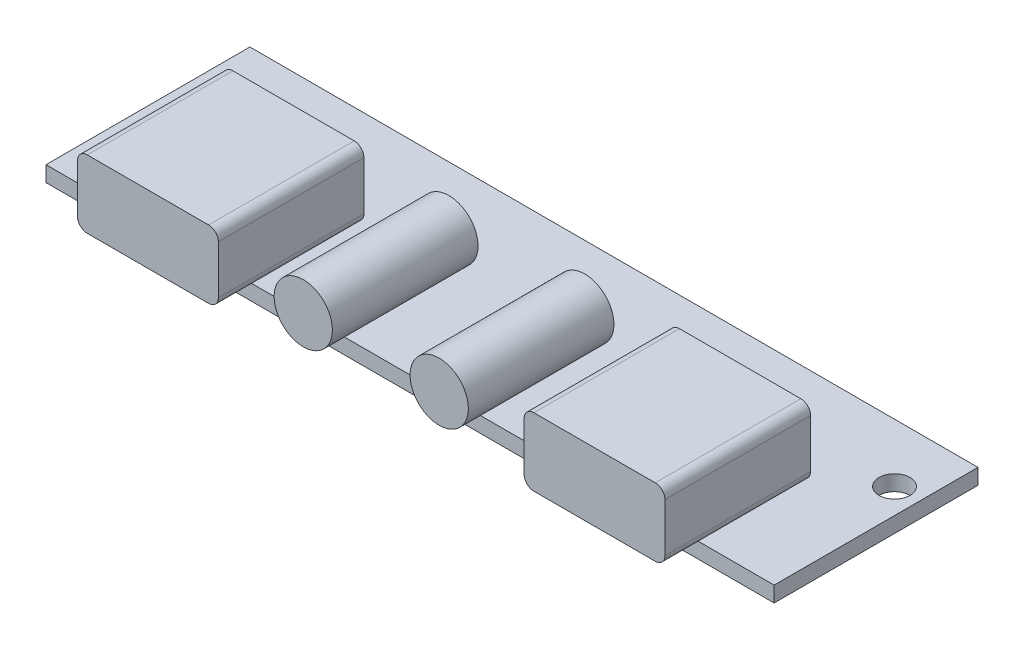
SolidWorks part; units mm, degrees
ref_plane "Front Plane" through (0, 0, 0) normal (0, 0, 1) x (1, 0, 0)
ref_plane "Top Plane" through (0, 0, 0) normal (0, 1, 0) x (1, 0, 0)
ref_plane "Right Plane" through (0, 0, 0) normal (1, 0, 0) x (0, 0, -1)
sketch "Sketch1" plane through (0, 0, 0) normal (0, 1, 0) x (1, 0, 0)
  line L1 (-37.5, 10.5) -> (37.5, 10.5)
  line L2 (-37.5, 10.5) -> (-37.5, -10.5)
  line L3 (-37.5, -10.5) -> (37.5, -10.5)
  line L4 (37.5, 10.5) -> (37.5, -10.5)
  line L5 (-37.5, 10.5) -> (37.5, -10.5) construction
  line L6 (-37.5, -10.5) -> (37.5, 10.5) construction
  point P0 (0, 0)
  dimension "D1" = 75
  dimension "D2" = 21
extrude "Boss-Extrude1" add sketch "Sketch1" along normal blind 1.6
ref_plane "Plane2" through (0, 0, 14.5) normal (0, 0, 1) x (1, 0, 0)
sketch "Sketch2" plane through (0, 0, 14.5) normal (0, 0, 1) x (1, 0, 0)
  line L0 (-37.5, 1.6) -> (37.5, 1.6) construction
  line L1 (-29.25, 8.6) -> (-16.75, 8.6)
  line L2 (-30.25, 7.6) -> (-30.25, 2.6)
  line L3 (-29.25, 1.6) -> (-16.75, 1.6)
  line L4 (-15.75, 7.6) -> (-15.75, 2.6)
  line L5 (-30.25, 8.6) -> (-15.75, 1.6) construction
  line L6 (-30.25, 1.6) -> (-15.75, 8.6) construction
  circle A1 centre (-7, 5.6) radius 3
  arc A2 (-29.25, 1.6) -> (-30.25, 2.6) centre (-29.25, 2.6) cw
  arc A3 (-15.75, 2.6) -> (-16.75, 1.6) centre (-16.75, 2.6) cw
  arc A4 (-16.75, 8.6) -> (-15.75, 7.6) centre (-16.75, 7.6) cw
  arc A5 (-29.25, 8.6) -> (-30.25, 7.6) centre (-29.25, 7.6) ccw
  point P0 (-23, 5.1)
  dimension "D3" = 6
  dimension "D7" = 1
  dimension "D1" = 14.5
  dimension "D2" = 7
  dimension "D4" = 0.5
  dimension "D5" = 7
  dimension "D6" = 23
  dimension "D8" = 0
extrude "Boss-Extrude2" add sketch "Sketch2" against normal blind 15 separate body
ref_plane "Plane1" through (0, 0, 0) normal (-1, 0, 0) x (0, 0, 1)
mirror "Mirror13" about plane through (0, 0, 0) normal (-1, 0, 0) of bodies 102 105
hole_wizard "M3 Clearance Hole1" positions "Sketch3" profile "Sketch4" hole size "M3" standard "AS" end condition up to next
sketch "Sketch3" plane through (0, 1.6, 0) normal (0, 1, 0) x (1, 0, 0)
  line L0 (-37.5, 10.5) -> (-37.5, -10.5) construction
  line L1 (37.5, 10.5) -> (-37.5, 10.5) construction
  point P0 (-34.9, 4.5)
  point P2 (34.9, 4.5)
  dimension "D1" = 69.8
  dimension "D2" = 2.6
  dimension "D3" = 6
sketch "Sketch4" plane through (-34.9, 1.6, -4.5) normal (1, 0, 0) x (0, 0, 1)
  line L0 (0, 0) -> (0, 1.6)
  line L1 (0, 1.6) -> (1.6, 1.6)
  line L2 (1.6, 1.6) -> (1.6, 0)
  line L5 (1.6, 0) -> (0, 0)
  line L11 (0, -6.35) -> (0, 107.95) construction
  dimension "Thru Hole Dia." = 3.2
  dimension "Thru Hole Depth" = 1.6
